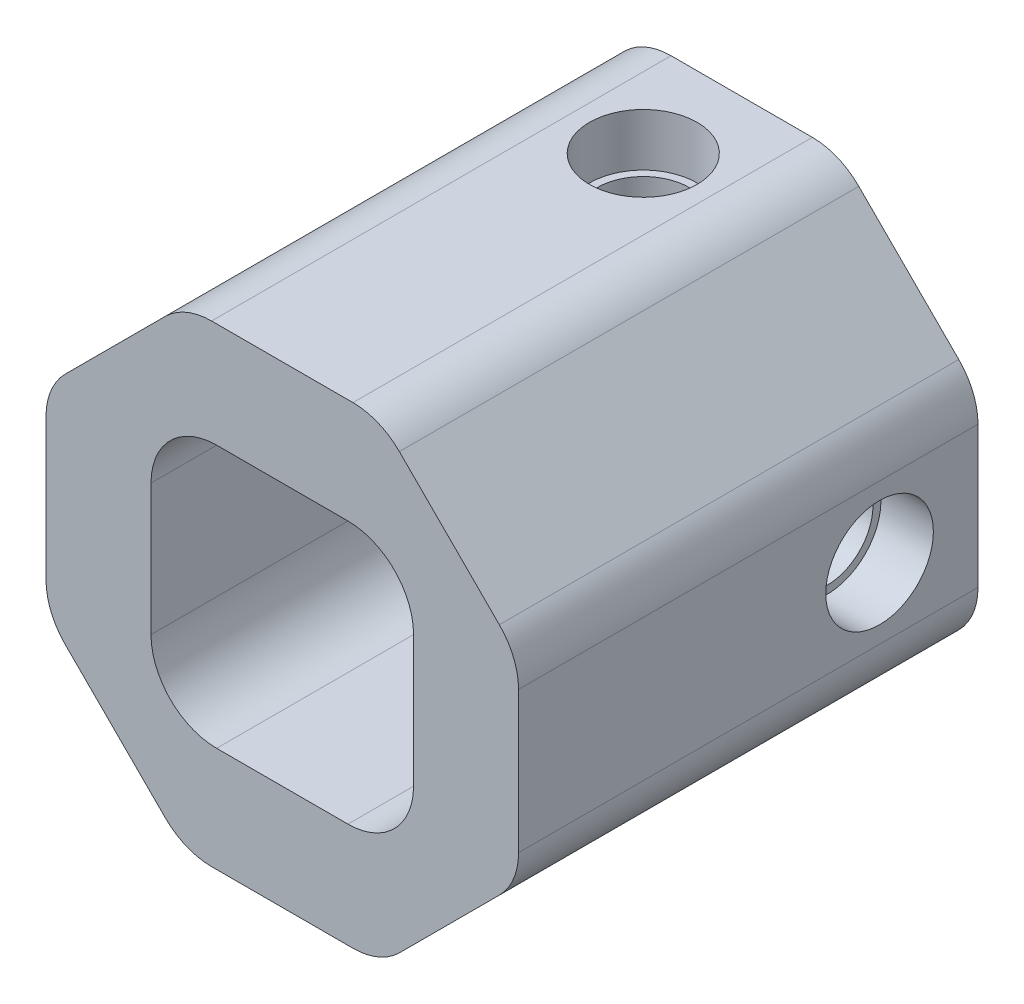
SolidWorks part; units mm, degrees
ref_plane "正面" through (0, 0, 0) normal (0, 0, 1) x (1, 0, 0)
ref_plane "平面" through (0, 0, 0) normal (0, 1, 0) x (1, 0, 0)
ref_plane "右側面" through (0, 0, 0) normal (1, 0, 0) x (0, 0, -1)
sketch "ｽｹｯﾁ1" plane through (0, 0, 0) normal (0, 0, 1) x (1, 0, 0)
  line L0 (7.4558, -18) -> (18, -7.4558)
  line L1 (-18, 7.4558) -> (-18, -7.4558)
  line L2 (-18, -7.4558) -> (-7.4558, -18)
  line L3 (-7.4558, -18) -> (7.4558, -18)
  line L4 (18, -7.4558) -> (18, 7.4558)
  line L5 (18, 7.4558) -> (7.4558, 18)
  line L6 (7.4558, 18) -> (-7.4558, 18)
  line L7 (-7.4558, 18) -> (-18, 7.4558)
  circle A0 centre (0, 0) radius 18 construction
  point P1 (0, -18)
  point P12 (-18, 0)
  dimension "D1" = 18
extrude "ﾎﾞｽ - 押し出し1" add sketch "ｽｹｯﾁ1" along normal mid plane 15
sketch "ｽｹｯﾁ2" plane through (0, 0, 7.5) normal (0, 0, 1) x (1, 0, 0)
  line L0 (7.4558, 18) -> (-7.4558, 18) construction
  line L1 (10, -10) -> (-10, -10)
  line L2 (10, -10) -> (10, 10)
  line L3 (10, 10) -> (-10, 10)
  line L4 (-10, -10) -> (-10, 10)
  line L5 (10, -10) -> (-10, 10) construction
  line L6 (10, 10) -> (-10, -10) construction
  line L7 (18, -7.4558) -> (18, 7.4558) construction
  point P0 (0, 0)
  dimension "D1" = 8
  dimension "D2" = 8
extrude "ｶｯﾄ - 押し出し1" cut sketch "ｽｹｯﾁ2" against normal through all both and the other way through all
fillet "ﾌｨﾚｯﾄ1" radius 5 4 edges at (10, -10, 0) (-10, -10, 0) (10, 10, 0) (-10, 10, 0)
fillet "ﾌｨﾚｯﾄ2" radius 5 8 edges at (18, -7.4558, 0) (7.4558, -18, 0) (-7.4558, -18, 0) (-18, -7.4558, 0) (18, 7.4558, 0) (7.4558, 18, 0) (-18, 7.4558, 0) (-7.4558, 18, 0)
sketch "ｽｹｯﾁ3" plane through (0, -18, 0) normal (0, -1, 0) x (1, 0, 0)
  circle A0 centre (0, 0) radius 4.1
  dimension "D1" = 8.2
extrude "ｶｯﾄ - 押し出し2" cut sketch "ｽｹｯﾁ3" against normal through all both and the other way through all
sketch "ｽｹｯﾁ4" plane through (18, 0, 0) normal (1, 0, 0) x (0, 0, -1)
  circle A0 centre (0, 0) radius 4.1
  dimension "D1" = 8.2
extrude "ｶｯﾄ - 押し出し3" cut sketch "ｽｹｯﾁ4" against normal through all both and the other way through all
sketch "ｽｹｯﾁ5" plane through (0, 0, 7.5) normal (0, 0, 1) x (1, 0, 0)
  line L0 (5, 10) -> (-5, 10) construction
  line L1 (10, -5) -> (10, 5) construction
  line L2 (-5, -10) -> (5, -10) construction
  line L3 (-10, 5) -> (-10, -5) construction
  line L4 (5, 10) -> (-5, 10)
  line L5 (10, -5) -> (10, 5)
  line L6 (-5, -10) -> (5, -10)
  line L7 (-10, 5) -> (-10, -5)
  line L8 (8.9203, -16.5355) -> (16.5355, -8.9203)
  line L9 (18, -5.3848) -> (18, 5.3848)
  line L10 (16.5355, 8.9203) -> (8.9203, 16.5355)
  line L11 (5.3848, 18) -> (-5.3848, 18)
  line L12 (-8.9203, 16.5355) -> (-16.5355, 8.9203)
  line L13 (-18, 5.3848) -> (-18, -5.3848)
  line L14 (-16.5355, -8.9203) -> (-8.9203, -16.5355)
  line L15 (-5.3848, -18) -> (5.3848, -18)
  line L16 (8.9203, -16.5355) -> (16.5355, -8.9203)
  line L17 (18, -5.3848) -> (18, 5.3848)
  line L18 (16.5355, 8.9203) -> (8.9203, 16.5355)
  line L19 (5.3848, 18) -> (-5.3848, 18)
  line L20 (-8.9203, 16.5355) -> (-16.5355, 8.9203)
  line L21 (-18, 5.3848) -> (-18, -5.3848)
  line L22 (-16.5355, -8.9203) -> (-8.9203, -16.5355)
  line L23 (-5.3848, -18) -> (5.3848, -18)
  arc A0 (-5, 10) -> (-10, 5) centre (-5, 5) ccw construction
  arc A1 (-5, 10) -> (-10, 5) centre (-5, 5) ccw
  arc A2 (10, 5) -> (5, 10) centre (5, 5) ccw construction
  arc A3 (5, -10) -> (10, -5) centre (5, -5) ccw construction
  arc A4 (-10, -5) -> (-5, -10) centre (-5, -5) ccw construction
  arc A5 (10, 5) -> (5, 10) centre (5, 5) ccw
  arc A6 (5, -10) -> (10, -5) centre (5, -5) ccw
  arc A7 (-10, -5) -> (-5, -10) centre (-5, -5) ccw
  arc A8 (16.5355, -8.9203) -> (18, -5.3848) centre (13, -5.3848) ccw
  arc A9 (18, 5.3848) -> (16.5355, 8.9203) centre (13, 5.3848) ccw
  arc A10 (8.9203, 16.5355) -> (5.3848, 18) centre (5.3848, 13) ccw
  arc A11 (-5.3848, 18) -> (-8.9203, 16.5355) centre (-5.3848, 13) ccw
  arc A12 (-16.5355, 8.9203) -> (-18, 5.3848) centre (-13, 5.3848) ccw
  arc A13 (-18, -5.3848) -> (-16.5355, -8.9203) centre (-13, -5.3848) ccw
  arc A14 (-8.9203, -16.5355) -> (-5.3848, -18) centre (-5.3848, -13) ccw
  arc A15 (5.3848, -18) -> (8.9203, -16.5355) centre (5.3848, -13) ccw
  arc A16 (16.5355, -8.9203) -> (18, -5.3848) centre (13, -5.3848) ccw
  arc A17 (18, 5.3848) -> (16.5355, 8.9203) centre (13, 5.3848) ccw
  arc A18 (8.9203, 16.5355) -> (5.3848, 18) centre (5.3848, 13) ccw
  arc A19 (-5.3848, 18) -> (-8.9203, 16.5355) centre (-5.3848, 13) ccw
  arc A20 (-16.5355, 8.9203) -> (-18, 5.3848) centre (-13, 5.3848) ccw
  arc A21 (-18, -5.3848) -> (-16.5355, -8.9203) centre (-13, -5.3848) ccw
  arc A22 (-8.9203, -16.5355) -> (-5.3848, -18) centre (-5.3848, -13) ccw
  arc A23 (5.3848, -18) -> (8.9203, -16.5355) centre (5.3848, -13) ccw
  dimension "D1" = 0
extrude "ﾎﾞｽ - 押し出し2" add sketch "ｽｹｯﾁ5" along normal blind 20
sketch "ｽｹｯﾁ6" plane through (0, -18, 0) normal (0, -1, 0) x (1, 0, 0)
  circle A0 centre (0, 0) radius 4.1 construction
  circle A1 centre (0, 0) radius 4.1
  circle A2 centre (0, 0) radius 3.5
  dimension "D1" = 7
extrude "ﾎﾞｽ - 押し出し3" add sketch "ｽｹｯﾁ6" against normal up to surface (4 mm away) from offset 4 up to face at (0, -10, -4.1) offset against normal yes
sketch "ｽｹｯﾁ7" plane through (18, 0, 0) normal (1, 0, 0) x (0, 0, -1)
  circle A0 centre (0, 0) radius 4.1 construction
  circle A1 centre (0, 0) radius 4.1
  circle A2 centre (0, 0) radius 3.5
  dimension "D1" = 7
extrude "ﾎﾞｽ - 押し出し4" add sketch "ｽｹｯﾁ7" along direction (1, 0, 0) on the side against the normal up to surface (4 mm away) from offset 4 offset against normal yes
sketch "ｽｹｯﾁ8" plane through (0, 18, 0) normal (0, 1, 0) x (1, 0, 0)
  circle A0 centre (0, 0) radius 4.1 construction
  circle A1 centre (0, 0) radius 4.1
  circle A2 centre (0, 0) radius 3.5
  dimension "D1" = 7
extrude "ﾎﾞｽ - 押し出し5" add sketch "ｽｹｯﾁ8" against normal up to surface (4 mm away) from offset 4 up to face at (0, 10, 4.1) offset against normal yes
sketch "ｽｹｯﾁ9" plane through (-18, 0, 0) normal (-1, 0, 0) x (0, 0, 1)
  circle A0 centre (0, 0) radius 4.1 construction
  circle A1 centre (0, 0) radius 4.1
  circle A2 centre (0, 0) radius 3.5
  dimension "D1" = 7
extrude "ﾎﾞｽ - 押し出し6" add sketch "ｽｹｯﾁ9" against normal up to surface (4 mm away) from offset 4 up to face at (-10, 0, 4.1)
